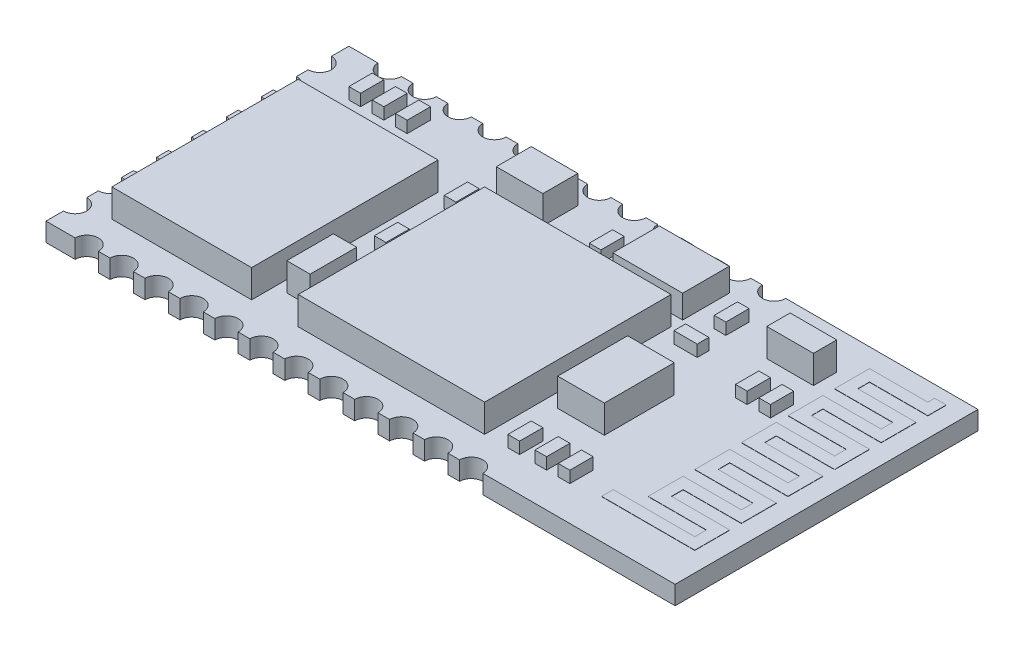
SolidWorks part; units mm, degrees
ref_plane "Front Plane" through (0, 0, 0) normal (0, 0, 1) x (1, 0, 0)
ref_plane "Top Plane" through (0, 0, 0) normal (0, 1, 0) x (1, 0, 0)
ref_plane "Right Plane" through (0, 0, 0) normal (1, 0, 0) x (0, 0, -1)
sketch "Sketch1" plane through (0, 0, 0) normal (0, 1, 0) x (1, 0, 0)
  line L1 (13.5, -6.5) -> (-13.5, -6.5)
  line L2 (13.5, -6.5) -> (13.5, 6.5)
  line L3 (13.5, 6.5) -> (-13.5, 6.5)
  line L4 (-13.5, -6.5) -> (-13.5, 6.5)
  line L5 (13.5, -6.5) -> (-13.5, 6.5) construction
  line L6 (13.5, 6.5) -> (-13.5, -6.5) construction
  point P0 (0, 0)
  dimension "D1" = 13
  dimension "D2" = 27
extrude "Boss-Extrude1" add sketch "Sketch1" along normal blind 0.8
sketch "Sketch2" plane through (0, 0.8, 0) normal (0, 1, 0) x (1, 0, 0)
  line L0 (-13.5, 6.5) -> (-13.5, -6.5) construction
  circle A0 centre (-13.5, 5.25) radius 0.5
  circle A1 centre (-13.5, 3.75) radius 0.5
  circle A2 centre (-13.5, 2.25) radius 0.5
  circle A3 centre (-13.5, 0.75) radius 0.5
  circle A4 centre (-13.5, -0.75) radius 0.5
  circle A5 centre (-13.5, -2.25) radius 0.5
  circle A6 centre (-13.5, -3.75) radius 0.5
  circle A7 centre (-13.5, -5.25) radius 0.5
  dimension "D1" = 1.25
  dimension "D2" = 2.75
  dimension "D3" = 4.25
  dimension "D4" = 5.75
  dimension "D5" = 7.25
  dimension "D6" = 8.75
  dimension "D7" = 10.25
  dimension "D8" = 11.75
extrude "Cut-Extrude7" cut sketch "Sketch2" against normal blind 2
sketch "Sketch9" plane through (0, 0.8, 0) normal (0, 1, 0) x (1, 0, 0)
  line L0 (13.5, 6.5) -> (-13.5, 6.5) construction
  line L1 (13.5, 0) -> (-13.5, 0) construction
  line L2 (13.5, -6.5) -> (13.5, 6.5) construction
  line L3 (-13.5, 0.25) -> (-13.5, -0.25) construction
  line L4 (-13.5, 6.5) -> (-13.5, 5.75) construction
  circle A0 centre (-11.75, 6.5) radius 0.5
  circle A1 centre (-10.25, 6.5) radius 0.5
  circle A2 centre (-8.75, 6.5) radius 0.5
  circle A3 centre (-7.25, 6.5) radius 0.5
  circle A4 centre (-5.75, 6.5) radius 0.5
  circle A5 centre (-4.25, 6.5) radius 0.5
  circle A6 centre (-2.75, 6.5) radius 0.5
  circle A7 centre (-1.25, 6.5) radius 0.5
  circle A8 centre (0.25, 6.5) radius 0.5
  circle A9 centre (1.75, 6.5) radius 0.5
  circle A10 centre (3.25, 6.5) radius 0.5
  circle A11 centre (4.75, 6.5) radius 0.5
  circle A12 centre (4.75, -6.5) radius 0.5
  circle A13 centre (3.25, -6.5) radius 0.5
  circle A14 centre (1.75, -6.5) radius 0.5
  circle A15 centre (0.25, -6.5) radius 0.5
  circle A16 centre (-1.25, -6.5) radius 0.5
  circle A17 centre (-2.75, -6.5) radius 0.5
  circle A18 centre (-4.25, -6.5) radius 0.5
  circle A19 centre (-5.75, -6.5) radius 0.5
  circle A20 centre (-7.25, -6.5) radius 0.5
  circle A21 centre (-8.75, -6.5) radius 0.5
  circle A22 centre (-10.25, -6.5) radius 0.5
  circle A23 centre (-11.75, -6.5) radius 0.5
  dimension "D1" = 1.75
  dimension "D2" = 1
  dimension "D3" = 12
  dimension "D4" = 1.5
extrude "Cut-Extrude9" cut sketch "Sketch9" against normal blind 2
sketch "Sketch10" plane through (0, 0.8, 0) normal (0, 1, 0) x (1, 0, 0)
  line L1 (-12.1586, 2.9835) -> (-6.1586, 2.9835)
  line L2 (-12.1586, 2.9835) -> (-12.1586, -5.0165)
  line L3 (-12.1586, -5.0165) -> (-6.1586, -5.0165)
  line L4 (-6.1586, 2.9835) -> (-6.1586, -5.0165)
  line L5 (-4.1586, 2.9835) -> (3.8414, 2.9835)
  line L6 (-4.1586, 2.9835) -> (-4.1586, -5.0165)
  line L7 (-4.1586, -5.0165) -> (3.8414, -5.0165)
  line L8 (3.8414, 2.9835) -> (3.8414, -5.0165)
  dimension "D1" = 6
  dimension "D2" = 8
  dimension "D3" = 2
  dimension "D4" = 8
  dimension "D5" = 2
extrude "Boss-Extrude2" add sketch "Sketch10" along normal blind 1.2
sketch "Sketch12" plane through (0, 0.8, 0) normal (0, 1, 0) x (1, 0, 0)
  line L0 (3.8414, 2.9835) -> (-4.1586, 2.9835) construction
  line L1 (0.8414, 5.4835) -> (3.8414, 5.4835)
  line L2 (0.8414, 5.4835) -> (0.8414, 3.4835)
  line L3 (0.8414, 3.4835) -> (3.8414, 3.4835)
  line L4 (3.8414, 5.4835) -> (3.8414, 3.4835)
  line L6 (3.8414, -5.0165) -> (3.8414, 2.9835) construction
  dimension "D1" = 2
  dimension "D2" = 3
  dimension "D3" = 0.5
  dimension "D4" = 0
extrude "Boss-Extrude3" add sketch "Sketch12" along normal blind 1
sketch "Sketch13" plane through (0, 0.8, 0) normal (0, 1, 0) x (1, 0, 0)
  line L1 (-4.6586, 5.4835) -> (-2.6586, 5.4835)
  line L2 (-4.6586, 5.4835) -> (-4.6586, 3.9835)
  line L3 (-4.6586, 3.9835) -> (-2.6586, 3.9835)
  line L4 (-2.6586, 5.4835) -> (-2.6586, 3.9835)
  line L5 (0.8414, 5.4835) -> (0.8414, 3.4835) construction
  line L7 (3.8414, 2.9835) -> (-4.1586, 2.9835) construction
  point P9 (0.8414, 4.4835)
  dimension "D1" = 1.5
  dimension "D2" = 2
  dimension "D3" = 3.5
  dimension "D4" = 1
extrude "Boss-Extrude4" add sketch "Sketch13" along normal blind 1.2
sketch "Sketch14" plane through (0, 0.8, 0) normal (0, 1, 0) x (1, 0, 0)
  line L0 (-13.5, 6.5) -> (-13.5, 5.75) construction
  line L1 (-11, 4.5) -> (-11.5, 4.5)
  line L2 (-11, 4.5) -> (-11, 5.5)
  line L3 (-11, 5.5) -> (-11.5, 5.5)
  line L4 (-11.5, 4.5) -> (-11.5, 5.5)
  line L5 (-10, 4.5) -> (-10, 5.5)
  line L6 (-10.5, 4.5) -> (-10.5, 5.5)
  line L7 (-10, 4.5) -> (-10.5, 4.5)
  line L8 (-9.5, 4.5) -> (-9.5, 5.5)
  line L9 (-9, 4.5) -> (-9.5, 4.5)
  line L10 (-9, 4.5) -> (-9, 5.5)
  line L11 (-9, 5.5) -> (-9.5, 5.5)
  line L12 (6.5, -5.0165) -> (6.5, -4.0165)
  line L13 (7.5, -5.0165) -> (7.5, -4.0165)
  line L14 (7.5, -4.0165) -> (7, -4.0165)
  line L15 (6.5, -4.0165) -> (6, -4.0165)
  line L16 (6.5, -5.0165) -> (6, -5.0165)
  line L17 (7.5, -5.0165) -> (7, -5.0165)
  line L18 (7, -5.0165) -> (7, -4.0165)
  line L19 (6, -5.0165) -> (6, -4.0165)
  line L20 (5.3414, -5.0165) -> (4.8414, -5.0165)
  line L21 (5.3414, -5.0165) -> (5.3414, -4.0165)
  line L22 (4.8414, -5.0165) -> (4.8414, -4.0165)
  line L23 (5.3414, -4.0165) -> (4.8414, -4.0165)
  line L24 (9.3661, 2.7256) -> (8.8661, 2.7256)
  line L25 (9.3661, 1.7256) -> (8.8661, 1.7256)
  line L26 (8.8661, 1.7256) -> (8.8661, 2.7256)
  line L27 (9.3661, 1.7256) -> (9.3661, 2.7256)
  line L28 (8.3661, 1.7256) -> (8.3661, 2.7256)
  line L29 (8.3661, 1.7256) -> (7.8661, 1.7256)
  line L30 (7.8661, 1.7256) -> (7.8661, 2.7256)
  line L31 (8.3661, 2.7256) -> (7.8661, 2.7256)
  line L32 (-5.4086, 2.5) -> (-5.4086, 3.5)
  line L33 (-4.9086, 2.5) -> (-5.4086, 2.5)
  line L34 (-4.9086, 3.5) -> (-5.4086, 3.5)
  line L35 (-4.9086, 2.5) -> (-4.9086, 3.5)
  line L36 (13.5, -6.5) -> (13.5, 6.5) construction
  line L38 (3.8414, -5.0165) -> (3.8414, 2.9835) construction
  line L39 (4.8414, 3.8366) -> (4.8414, 4.8366)
  line L40 (-4.9086, 0.5) -> (-5.4086, 0.5)
  line L41 (-5.4086, -0.5) -> (-5.4086, 0.5)
  line L42 (-4.9086, -0.5) -> (-4.9086, 0.5)
  line L43 (-4.9086, -0.5) -> (-5.4086, -0.5)
  line L44 (-4.9086, -4.1379) -> (-4.9086, -2.6379)
  line L45 (-4.9086, -2.6379) -> (-5.4086, -2.6379)
  line L46 (-5.4086, -4.1379) -> (-5.4086, -2.6379)
  line L47 (-4.9086, -4.1379) -> (-5.4086, -4.1379)
  line L48 (-6.1586, -5.0165) -> (-6.1586, 2.9835) construction
  line L49 (5.3414, 4.8366) -> (4.8414, 4.8366)
  line L50 (5.3414, 3.8366) -> (5.3414, 4.8366)
  line L51 (5.3414, 3.8366) -> (4.8414, 3.8366)
  line L52 (-0.0202, 3.8366) -> (-0.5202, 3.8366)
  line L53 (-0.0202, 4.8366) -> (-0.5202, 4.8366)
  line L54 (-0.0202, 3.8366) -> (-0.0202, 4.8366)
  line L55 (-0.5202, 3.8366) -> (-0.5202, 4.8366)
  line L56 (7.5, 4.196) -> (7.5, 3.696)
  line L57 (9, 3.696) -> (7.5, 3.696)
  line L58 (9, 4.196) -> (7.5, 4.196)
  line L59 (9, 4.196) -> (9, 3.696)
  line L60 (5.5459, 2.9031) -> (4.5459, 2.9031)
  line L61 (4.5459, -0.6918) -> (5.5459, -0.6918)
  line L62 (4.5459, -0.6918) -> (4.5459, -2.6918)
  line L63 (4.5459, -2.6918) -> (5.5459, -2.6918)
  line L64 (5.5459, -0.6918) -> (5.5459, -2.6918)
  line L65 (5.5459, 2.4031) -> (4.5459, 2.4031)
  line L66 (4.5459, 2.9031) -> (4.5459, 2.4031)
  line L67 (5.5459, 2.9031) -> (5.5459, 2.4031)
  line L68 (-10.5, 5.5) -> (-10, 5.5)
  line L69 (-9.5, 5.5) -> (-9, 5.5)
  dimension "D1" = 0.5
  dimension "D2" = 1
  dimension "D3" = 2
  dimension "D4" = 1
  dimension "D5" = 1
  dimension "D6" = 0.5
  dimension "D7" = 1
  dimension "D8" = 0.5
  dimension "D9" = 0.5
  dimension "D10" = 0.5
  dimension "D11" = 0.5
  dimension "D12" = 1
  dimension "D13" = 0.5
  dimension "D14" = 0.75
  dimension "D15" = 1
  dimension "D16" = 1
  dimension "D17" = 0.5
  dimension "D18" = 1
  dimension "D19" = 0.5
  dimension "D20" = 6
  dimension "D21" = 0.75
  dimension "D22" = 0.75
  dimension "D24" = 1
  dimension "D25" = 2
  dimension "D26" = 1
  dimension "D27" = 1.5
  dimension "D28" = 1
  dimension "D29" = 2
extrude "Boss-Extrude6" add sketch "Sketch14" along normal blind 0.5 contours L10 L11 L8 L9 | L43 L42 L40 L41 | L51 L50 L49 L39 | L28 L31 L30 L29 | L25 L27 L24 L26 | L19 L16 L12 L15 | L2 L3 L4 L1 | L6 L68 L5 L7 | L54 L53 L55 L52 | L32 L34 L35 L33 | L60 L66 L65 L67 | L18 L14 L13 L17 | L21 L23 L22 L20
sketch "Sketch15" plane through (0, 0.8, 0) normal (0, 1, 0) x (1, 0, 0)
  line L0 (7.0844, 3.8532) -> (7.0844, 4.8532)
  line L1 (-5.6604, -2.0048) -> (-4.6604, -2.0048)
  line L2 (-5.6604, -2.0048) -> (-5.6604, -4.0048)
  line L3 (-5.6604, -4.0048) -> (-4.6604, -4.0048)
  line L4 (-4.6604, -2.0048) -> (-4.6604, -4.0048)
  line L5 (7.0844, 3.8532) -> (9.0844, 3.8532)
  line L6 (7.0844, 4.8532) -> (9.0844, 4.8532)
  line L7 (9.0844, 3.8532) -> (9.0844, 4.8532)
  dimension "D1" = 1
  dimension "D2" = 2
  dimension "D3" = 1
  dimension "D4" = 2
extrude "Boss-Extrude7" add sketch "Sketch15" along normal blind 1.2
sketch "Sketch16" plane through (0, 0.8, 0) normal (0, 1, 0) x (1, 0, 0)
  line L1 (4.4442, 0.5186) -> (6.4442, 0.5186)
  line L2 (4.4442, 0.5186) -> (4.4442, -2.4814)
  line L3 (4.4442, -2.4814) -> (6.4442, -2.4814)
  line L4 (6.4442, 0.5186) -> (6.4442, -2.4814)
  dimension "D1" = 2
  dimension "D2" = 3
extrude "Boss-Extrude8" add sketch "Sketch16" along normal blind 1.2
sketch "Sketch17" plane through (0, 0.8, 0) normal (0, 1, 0) x (1, 0, 0)
  line L0 (12.1639, 5.6806) -> (9.6639, 5.6806)
  line L1 (9.6639, 5.6806) -> (9.6639, 4.1806)
  line L2 (10.1639, 5.1806) -> (12.6639, 5.1806)
  line L3 (10.1639, 5.1806) -> (10.1639, 4.6806)
  line L4 (9.6639, 4.1806) -> (12.1639, 4.1806)
  line L5 (9.6639, 3.6806) -> (9.6639, 2.1806)
  line L6 (10.1639, 3.1806) -> (10.1639, 2.6806)
  line L7 (12.1639, 3.6806) -> (9.6639, 3.6806)
  line L8 (10.1639, 3.1806) -> (12.6639, 3.1806)
  line L9 (9.6639, 2.1806) -> (12.1639, 2.1806)
  line L10 (12.6639, 3.1806) -> (12.6639, 4.6806)
  line L11 (10.1639, 4.6806) -> (12.6639, 4.6806)
  line L12 (12.1639, 4.1806) -> (12.1639, 3.6806)
  line L13 (10.1639, 2.6806) -> (12.6639, 2.6806)
  line L14 (9.6639, 1.6806) -> (9.6639, 0.1806)
  line L15 (10.1639, -0.8194) -> (12.6639, -0.8194)
  line L16 (12.1639, 0.1806) -> (12.1639, -0.3194)
  line L17 (9.6639, -0.3194) -> (9.6639, -1.8194)
  line L18 (9.6639, 0.1806) -> (12.1639, 0.1806)
  line L19 (9.6639, -1.8194) -> (12.1639, -1.8194)
  line L20 (10.1639, -0.8194) -> (10.1639, -1.3194)
  line L21 (12.6639, -0.8194) -> (12.6639, 0.6806)
  line L22 (10.1639, 1.1806) -> (12.6639, 1.1806)
  line L23 (12.1639, -0.3194) -> (9.6639, -0.3194)
  line L24 (12.1639, 1.6806) -> (9.6639, 1.6806)
  line L25 (10.1639, 0.6806) -> (12.6639, 0.6806)
  line L26 (10.1639, -1.3194) -> (12.6639, -1.3194)
  line L27 (10.1639, 1.1806) -> (10.1639, 0.6806)
  line L28 (12.1639, 1.6806) -> (12.1639, 2.1806)
  line L29 (12.6639, 2.6806) -> (12.6639, 1.1806)
  line L30 (12.6639, -2.8194) -> (12.6639, -1.3194)
  line L31 (9.6639, -3.8194) -> (12.1639, -3.8194)
  line L32 (10.1639, -3.3194) -> (12.6639, -3.3194)
  line L33 (10.1639, -2.8194) -> (12.6639, -2.8194)
  line L34 (12.1639, -2.3194) -> (9.6639, -2.3194)
  line L35 (12.1639, -1.8194) -> (12.1639, -2.3194)
  line L36 (9.6639, -2.3194) -> (9.6639, -3.8194)
  line L37 (10.1639, -2.8194) -> (10.1639, -3.3194)
  line L38 (8.6639, -4.8194) -> (12.6639, -4.8194)
  line L39 (12.1639, -3.8194) -> (12.1639, -4.3194)
  line L40 (12.1639, -4.3194) -> (8.6639, -4.3194)
  line L41 (12.6639, -4.8194) -> (12.6639, -3.3194)
  line L42 (8.6639, -4.8194) -> (8.6639, -4.3194)
  line L43 (12.6639, 5.1806) -> (12.6639, 5.975)
  line L44 (12.6639, 5.975) -> (12.1639, 5.975)
  line L45 (12.1639, 5.975) -> (12.1639, 5.6806)
  dimension "D1" = 2.5
  dimension "D3" = 2.5
  dimension "D4" = 0.5
  dimension "D5" = 0.5
  dimension "D6" = 0.5
  dimension "D7" = 2.5
  dimension "D8" = 2.5
  dimension "D9" = 0.5
  dimension "D10" = 1.5
  dimension "D11" = 0.5
  dimension "D12" = 2.5
  dimension "D13" = 1.5
  dimension "D14" = 2.5
  dimension "D15" = 0.5
  dimension "D16" = 0.5
  dimension "D17" = 0.5
  dimension "D18" = 2.5
  dimension "D19" = 2.5
  dimension "D20" = 0.5
  dimension "D21" = 1.5
  dimension "D22" = 0.5
  dimension "D23" = 0.5
  dimension "D24" = 2.5
  dimension "D25" = 1.5
  dimension "D26" = 0.5
  dimension "D27" = 0.5
  dimension "D28" = 4
  dimension "D29" = 1.5
  dimension "D30" = 0.5
  dimension "D31" = 0.5
  dimension "D32" = 3.5
extrude "Boss-Extrude9" add sketch "Sketch17" along normal blind 0.01
